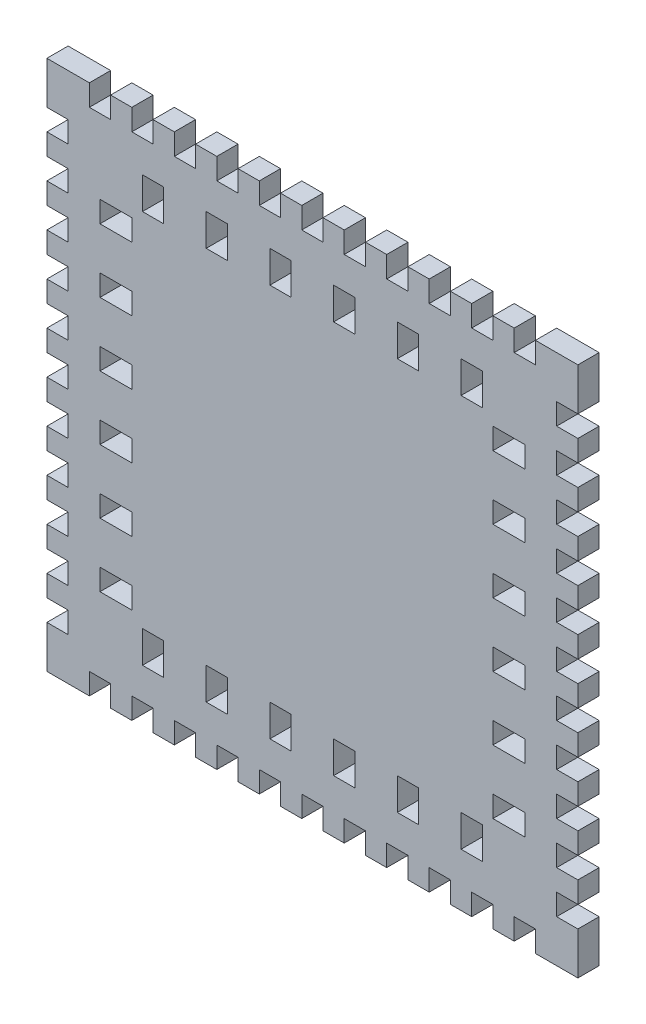
SolidWorks part; units mm, degrees
ref_plane "Front Plane" through (0, 0, 0) normal (0, 0, 1) x (1, 0, 0)
ref_plane "Top Plane" through (0, 0, 0) normal (0, 1, 0) x (1, 0, 0)
ref_plane "Right Plane" through (0, 0, 0) normal (1, 0, 0) x (0, 0, -1)
sketch "Sketch1" plane through (0, 0, 0) normal (0, 0, 1) x (1, 0, 0)
  line L1008 (28.5, 285) -> (28.5, 289.5)
  line L1009 (28.5, 289.5) -> (25.5, 289.5)
  line L1010 (25.5, 289.5) -> (25.5, 285)
  line L1011 (25.5, 285) -> (28.5, 285)
  line L1012 (16.5, 289.5) -> (16.5, 285)
  line L1013 (16.5, 285) -> (19.5, 285)
  line L1014 (19.5, 285) -> (19.5, 289.5)
  line L1015 (19.5, 289.5) -> (16.5, 289.5)
  line L1016 (10.5, 280.5) -> (15, 280.5)
  line L1017 (15, 280.5) -> (15, 283.5)
  line L1018 (15, 283.5) -> (10.5, 283.5)
  line L1019 (10.5, 283.5) -> (10.5, 280.5)
  line L1020 (10.5, 271.5) -> (15, 271.5)
  line L1021 (15, 271.5) -> (15, 274.5)
  line L1022 (15, 274.5) -> (10.5, 274.5)
  line L1023 (10.5, 274.5) -> (10.5, 271.5)
  line L1024 (10.5, 262.5) -> (15, 262.5)
  line L1025 (15, 262.5) -> (15, 265.5)
  line L1026 (15, 265.5) -> (10.5, 265.5)
  line L1027 (10.5, 265.5) -> (10.5, 262.5)
  line L1028 (10.5, 253.5) -> (15, 253.5)
  line L1029 (15, 253.5) -> (15, 256.5)
  line L1030 (15, 256.5) -> (10.5, 256.5)
  line L1031 (10.5, 256.5) -> (10.5, 253.5)
  line L1032 (10.5, 244.5) -> (15, 244.5)
  line L1033 (15, 244.5) -> (15, 247.5)
  line L1034 (15, 247.5) -> (10.5, 247.5)
  line L1035 (10.5, 247.5) -> (10.5, 244.5)
  line L1036 (10.5, 235.5) -> (15, 235.5)
  line L1037 (15, 235.5) -> (15, 238.5)
  line L1038 (15, 238.5) -> (10.5, 238.5)
  line L1039 (10.5, 238.5) -> (10.5, 235.5)
  line L1040 (19.5, 229.5) -> (19.5, 234)
  line L1041 (19.5, 234) -> (16.5, 234)
  line L1042 (16.5, 234) -> (16.5, 229.5)
  line L1043 (16.5, 229.5) -> (19.5, 229.5)
  line L1044 (28.5, 229.5) -> (28.5, 234)
  line L1045 (28.5, 234) -> (25.5, 234)
  line L1046 (25.5, 234) -> (25.5, 229.5)
  line L1047 (25.5, 229.5) -> (28.5, 229.5)
  line L1048 (37.5, 229.5) -> (37.5, 234)
  line L1049 (37.5, 234) -> (34.5, 234)
  line L1050 (34.5, 234) -> (34.5, 229.5)
  line L1051 (34.5, 229.5) -> (37.5, 229.5)
  line L1052 (46.5, 229.5) -> (46.5, 234)
  line L1053 (46.5, 234) -> (43.5, 234)
  line L1054 (43.5, 234) -> (43.5, 229.5)
  line L1055 (43.5, 229.5) -> (46.5, 229.5)
  line L1056 (55.5, 229.5) -> (55.5, 234)
  line L1057 (55.5, 234) -> (52.5, 234)
  line L1058 (52.5, 234) -> (52.5, 229.5)
  line L1059 (52.5, 229.5) -> (55.5, 229.5)
  line L1060 (64.5, 229.5) -> (64.5, 234)
  line L1061 (64.5, 234) -> (61.5, 234)
  line L1062 (61.5, 234) -> (61.5, 229.5)
  line L1063 (61.5, 229.5) -> (64.5, 229.5)
  line L1064 (70.5, 238.5) -> (66, 238.5)
  line L1065 (66, 238.5) -> (66, 235.5)
  line L1066 (66, 235.5) -> (70.5, 235.5)
  line L1067 (70.5, 235.5) -> (70.5, 238.5)
  line L1068 (70.5, 247.5) -> (66, 247.5)
  line L1069 (66, 247.5) -> (66, 244.5)
  line L1070 (66, 244.5) -> (70.5, 244.5)
  line L1071 (70.5, 244.5) -> (70.5, 247.5)
  line L1072 (70.5, 256.5) -> (66, 256.5)
  line L1073 (66, 256.5) -> (66, 253.5)
  line L1074 (66, 253.5) -> (70.5, 253.5)
  line L1075 (70.5, 253.5) -> (70.5, 256.5)
  line L1076 (70.5, 265.5) -> (66, 265.5)
  line L1077 (66, 265.5) -> (66, 262.5)
  line L1078 (66, 262.5) -> (70.5, 262.5)
  line L1079 (70.5, 262.5) -> (70.5, 265.5)
  line L1080 (70.5, 274.5) -> (66, 274.5)
  line L1081 (66, 274.5) -> (66, 271.5)
  line L1082 (66, 271.5) -> (70.5, 271.5)
  line L1083 (70.5, 271.5) -> (70.5, 274.5)
  line L1084 (70.5, 283.5) -> (66, 283.5)
  line L1085 (66, 283.5) -> (66, 280.5)
  line L1086 (66, 280.5) -> (70.5, 280.5)
  line L1087 (70.5, 280.5) -> (70.5, 283.5)
  line L1088 (61.5, 289.5) -> (61.5, 285)
  line L1089 (61.5, 285) -> (64.5, 285)
  line L1090 (64.5, 285) -> (64.5, 289.5)
  line L1091 (64.5, 289.5) -> (61.5, 289.5)
  line L1092 (52.5, 289.5) -> (52.5, 285)
  line L1093 (52.5, 285) -> (55.5, 285)
  line L1094 (55.5, 285) -> (55.5, 289.5)
  line L1095 (55.5, 289.5) -> (52.5, 289.5)
  line L1096 (43.5, 289.5) -> (43.5, 285)
  line L1097 (43.5, 285) -> (46.5, 285)
  line L1098 (46.5, 285) -> (46.5, 289.5)
  line L1099 (46.5, 289.5) -> (43.5, 289.5)
  line L1100 (34.5, 289.5) -> (34.5, 285)
  line L1101 (34.5, 285) -> (37.5, 285)
  line L1102 (37.5, 285) -> (37.5, 289.5)
  line L1103 (37.5, 289.5) -> (34.5, 289.5)
  line L1104 (63, 222) -> (63, 225)
  line L1105 (63, 225) -> (66, 225)
  line L1106 (66, 225) -> (66, 222)
  line L1107 (66, 222) -> (69, 222)
  line L1108 (69, 222) -> (69, 225)
  line L1109 (69, 225) -> (72, 225)
  line L1110 (72, 225) -> (72, 222)
  line L1111 (72, 222) -> (78, 222)
  line L1112 (78, 222) -> (78, 228)
  line L1113 (78, 228) -> (75, 228)
  line L1114 (75, 228) -> (75, 231)
  line L1115 (75, 231) -> (78, 231)
  line L1116 (78, 231) -> (78, 234)
  line L1117 (78, 234) -> (75, 234)
  line L1118 (75, 234) -> (75, 237)
  line L1119 (75, 237) -> (78, 237)
  line L1120 (78, 237) -> (78, 240)
  line L1121 (78, 240) -> (75, 240)
  line L1122 (75, 240) -> (75, 243)
  line L1123 (75, 243) -> (78, 243)
  line L1124 (78, 243) -> (78, 246)
  line L1125 (78, 246) -> (75, 246)
  line L1126 (75, 246) -> (75, 249)
  line L1127 (75, 249) -> (78, 249)
  line L1128 (78, 249) -> (78, 252)
  line L1129 (78, 252) -> (75, 252)
  line L1130 (75, 252) -> (75, 255)
  line L1131 (75, 255) -> (78, 255)
  line L1132 (78, 255) -> (78, 258)
  line L1133 (78, 258) -> (75, 258)
  line L1134 (75, 258) -> (75, 261)
  line L1135 (75, 261) -> (78, 261)
  line L1136 (78, 261) -> (78, 264)
  line L1137 (78, 264) -> (75, 264)
  line L1138 (75, 264) -> (75, 267)
  line L1139 (75, 267) -> (78, 267)
  line L1140 (78, 267) -> (78, 270)
  line L1141 (78, 270) -> (75, 270)
  line L1142 (75, 270) -> (75, 273)
  line L1143 (75, 273) -> (78, 273)
  line L1144 (78, 273) -> (78, 276)
  line L1145 (78, 276) -> (75, 276)
  line L1146 (75, 276) -> (75, 279)
  line L1147 (75, 279) -> (78, 279)
  line L1148 (78, 279) -> (78, 282)
  line L1149 (78, 282) -> (75, 282)
  line L1150 (75, 282) -> (75, 285)
  line L1151 (75, 285) -> (78, 285)
  line L1152 (78, 285) -> (78, 288)
  line L1153 (78, 288) -> (75, 288)
  line L1154 (75, 288) -> (75, 291)
  line L1155 (75, 291) -> (78, 291)
  line L1156 (78, 291) -> (78, 297)
  line L1157 (78, 297) -> (72, 297)
  line L1158 (72, 297) -> (72, 294)
  line L1159 (72, 294) -> (69, 294)
  line L1160 (69, 294) -> (69, 297)
  line L1161 (69, 297) -> (66, 297)
  line L1162 (66, 297) -> (66, 294)
  line L1163 (66, 294) -> (63, 294)
  line L1164 (63, 294) -> (63, 297)
  line L1165 (63, 297) -> (60, 297)
  line L1166 (60, 297) -> (60, 294)
  line L1167 (60, 294) -> (57, 294)
  line L1168 (57, 294) -> (57, 297)
  line L1169 (57, 297) -> (54, 297)
  line L1170 (54, 297) -> (54, 294)
  line L1171 (54, 294) -> (51, 294)
  line L1172 (51, 294) -> (51, 297)
  line L1173 (51, 297) -> (48, 297)
  line L1174 (48, 297) -> (48, 294)
  line L1175 (48, 294) -> (45, 294)
  line L1176 (45, 294) -> (45, 297)
  line L1177 (45, 297) -> (42, 297)
  line L1178 (42, 297) -> (42, 294)
  line L1179 (42, 294) -> (39, 294)
  line L1180 (39, 294) -> (39, 297)
  line L1181 (39, 297) -> (36, 297)
  line L1182 (36, 297) -> (36, 294)
  line L1183 (36, 294) -> (33, 294)
  line L1184 (33, 294) -> (33, 297)
  line L1185 (33, 297) -> (30, 297)
  line L1186 (30, 297) -> (30, 294)
  line L1187 (30, 294) -> (27, 294)
  line L1188 (27, 294) -> (27, 297)
  line L1189 (27, 297) -> (24, 297)
  line L1190 (24, 297) -> (24, 294)
  line L1191 (24, 294) -> (21, 294)
  line L1192 (21, 294) -> (21, 297)
  line L1193 (21, 297) -> (18, 297)
  line L1194 (18, 297) -> (18, 294)
  line L1195 (18, 294) -> (15, 294)
  line L1196 (15, 294) -> (15, 297)
  line L1197 (15, 297) -> (12, 297)
  line L1198 (12, 297) -> (12, 294)
  line L1199 (12, 294) -> (9, 294)
  line L1200 (9, 294) -> (9, 297)
  line L1201 (9, 297) -> (3, 297)
  line L1202 (3, 297) -> (3, 291)
  line L1203 (3, 291) -> (6, 291)
  line L1204 (6, 291) -> (6, 288)
  line L1205 (6, 288) -> (3, 288)
  line L1206 (3, 288) -> (3, 285)
  line L1207 (3, 285) -> (6, 285)
  line L1208 (6, 285) -> (6, 282)
  line L1209 (6, 282) -> (3, 282)
  line L1210 (3, 282) -> (3, 279)
  line L1211 (3, 279) -> (6, 279)
  line L1212 (6, 279) -> (6, 276)
  line L1213 (6, 276) -> (3, 276)
  line L1214 (3, 276) -> (3, 273)
  line L1215 (3, 273) -> (6, 273)
  line L1216 (6, 273) -> (6, 270)
  line L1217 (6, 270) -> (3, 270)
  line L1218 (3, 270) -> (3, 267)
  line L1219 (3, 267) -> (6, 267)
  line L1220 (6, 267) -> (6, 264)
  line L1221 (6, 264) -> (3, 264)
  line L1222 (3, 264) -> (3, 261)
  line L1223 (3, 261) -> (6, 261)
  line L1224 (6, 261) -> (6, 258)
  line L1225 (6, 258) -> (3, 258)
  line L1226 (3, 258) -> (3, 255)
  line L1227 (3, 255) -> (6, 255)
  line L1228 (6, 255) -> (6, 252)
  line L1229 (6, 252) -> (3, 252)
  line L1230 (3, 252) -> (3, 249)
  line L1231 (3, 249) -> (6, 249)
  line L1232 (6, 249) -> (6, 246)
  line L1233 (6, 246) -> (3, 246)
  line L1234 (3, 246) -> (3, 243)
  line L1235 (3, 243) -> (6, 243)
  line L1236 (6, 243) -> (6, 240)
  line L1237 (6, 240) -> (3, 240)
  line L1238 (3, 240) -> (3, 237)
  line L1239 (3, 237) -> (6, 237)
  line L1240 (6, 237) -> (6, 234)
  line L1241 (6, 234) -> (3, 234)
  line L1242 (3, 234) -> (3, 231)
  line L1243 (3, 231) -> (6, 231)
  line L1244 (6, 231) -> (6, 228)
  line L1245 (6, 228) -> (3, 228)
  line L1246 (3, 228) -> (3, 222)
  line L1247 (3, 222) -> (9, 222)
  line L1248 (9, 222) -> (9, 225)
  line L1249 (9, 225) -> (12, 225)
  line L1250 (12, 225) -> (12, 222)
  line L1251 (12, 222) -> (15, 222)
  line L1252 (15, 222) -> (15, 225)
  line L1253 (15, 225) -> (18, 225)
  line L1254 (18, 225) -> (18, 222)
  line L1255 (18, 222) -> (21, 222)
  line L1256 (21, 222) -> (21, 225)
  line L1257 (21, 225) -> (24, 225)
  line L1258 (24, 225) -> (24, 222)
  line L1259 (24, 222) -> (27, 222)
  line L1260 (27, 222) -> (27, 225)
  line L1261 (27, 225) -> (30, 225)
  line L1262 (30, 225) -> (30, 222)
  line L1263 (30, 222) -> (33, 222)
  line L1264 (33, 222) -> (33, 225)
  line L1265 (33, 225) -> (36, 225)
  line L1266 (36, 225) -> (36, 222)
  line L1267 (36, 222) -> (39, 222)
  line L1268 (39, 222) -> (39, 225)
  line L1269 (39, 225) -> (42, 225)
  line L1270 (42, 225) -> (42, 222)
  line L1271 (42, 222) -> (45, 222)
  line L1272 (45, 222) -> (45, 225)
  line L1273 (45, 225) -> (48, 225)
  line L1274 (48, 225) -> (48, 222)
  line L1275 (48, 222) -> (51, 222)
  line L1276 (51, 222) -> (51, 225)
  line L1277 (51, 225) -> (54, 225)
  line L1278 (54, 225) -> (54, 222)
  line L1279 (54, 222) -> (57, 222)
  line L1280 (57, 222) -> (57, 225)
  line L1281 (57, 225) -> (60, 225)
  line L1282 (60, 225) -> (60, 222)
  line L1283 (60, 222) -> (63, 222)
extrude "Boss-Extrude1" add sketch "Sketch1" along normal blind 3
